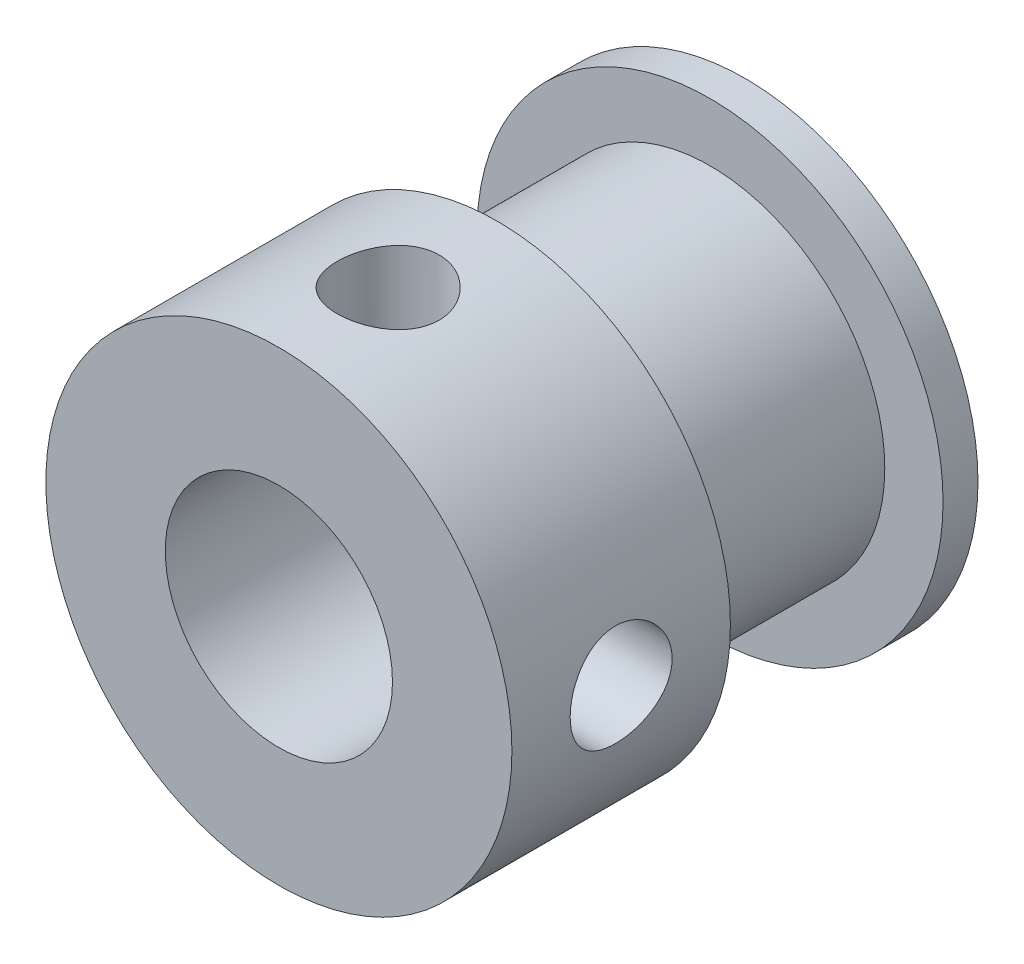
SolidWorks part; units mm, degrees
ref_plane "Front Plane" through (0, 0, 0) normal (0, 0, 1) x (1, 0, 0)
ref_plane "Top Plane" through (0, 0, 0) normal (0, 1, 0) x (1, 0, 0)
ref_plane "Right Plane" through (0, 0, 0) normal (1, 0, 0) x (0, 0, -1)
sketch "Sketch2" plane through (0, 0, 0) normal (0, 0, 1) x (1, 0, 0)
  circle A0 centre (0, 0) radius 8
  circle A1 centre (0, 0) radius 3.9
  dimension "D1" = 16
  dimension "D2" = 7.8
extrude "Boss-Extrude1" add sketch "Sketch2" along normal blind 16
ref_plane "Plane1" through (0, 0, 1.2) normal (0, 0, 1) x (1, 0, 0)
sketch "Sketch3" plane through (0, 0, 1.2) normal (0, 0, 1) x (1, 0, 0)
  circle A0 centre (0, 0) radius 6
  dimension "D1" = 12
ref_plane "Plane2" through (0, 0, 8.5) normal (0, 0, 1) x (1, 0, 0)
extrude "Cut-Extrude1" cut sketch "Sketch3" along normal up to surface (7.3 mm away) flip side to cut up to plane "Plane2"
sketch "Sketch4" plane through (0, 0, 16) normal (0, 0, 1) x (1, 0, 0)
  line L0 (0, 0) -> (0, 8) construction
  line L1 (0, 0) -> (8, 0) construction
  line L2 (0, 0) -> (0, -8) construction
  line L3 (0, 0) -> (-8, 0) construction
  circle A0 centre (0, 0) radius 8 construction
ref_plane "Plane3" through (0, 8, 0) normal (0, 1, 0) x (1, 0, 0)
ref_plane "Plane4" through (0, -8, 0) normal (0, 1, 0) x (1, 0, 0)
ref_plane "Plane5" through (8, 0, 0) normal (1, 0, 0) x (0, 0, -1)
sketch "Sketch5" plane through (0, 8, 0) normal (0, 1, 0) x (1, 0, 0)
  line L0 (0, -16) -> (0, -8.5) construction
  line L1 (0, -16) -> (-8, -16) construction
  line L2 (-8.8, -8.5) -> (8.8, -8.5) construction
  line L3 (-8, -12.25) -> (8, -12.25) construction
  line L5 (8, -8.8) -> (8, 8.8) construction
  circle A0 centre (0, -12.25) radius 1.75
  point P12 (0, -12.25)
  dimension "D1" = 3.5
sketch "Sketch6" plane through (8, 0, 0) normal (1, 0, 0) x (0, 0, -1)
  line L0 (-16, 0) -> (-8.5, 0) construction
  line L1 (-16, 0) -> (-16, -8) construction
  line L2 (-16, 0) -> (-16, 8) construction
  line L3 (-8.5, 8.8) -> (-8.5, -8.8) construction
  line L4 (-12.25, -8) -> (-12.25, 8) construction
  circle A0 centre (-12.25, 0) radius 1.75
  point P13 (-12.25, 0)
  dimension "D1" = 3.5
extrude "Cut-Extrude2" cut sketch "Sketch6" against normal up to next
extrude "Cut-Extrude3" cut sketch "Sketch5" against normal up to next
